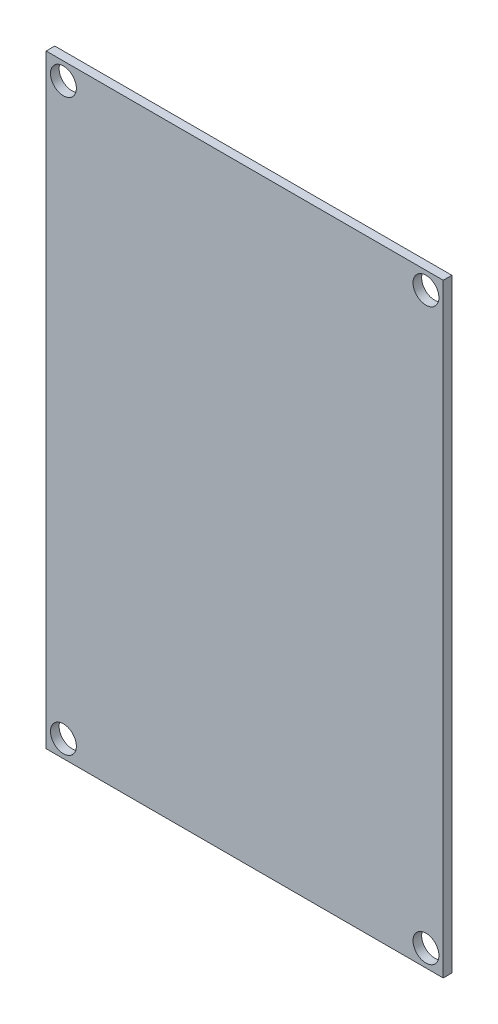
SolidWorks part; units mm, degrees
ref_plane "Alzado" through (0, 0, 0) normal (0, 0, 1) x (1, 0, 0)
ref_plane "Planta" through (0, 0, 0) normal (0, 1, 0) x (1, 0, 0)
ref_plane "Vista lateral" through (0, 0, 0) normal (1, 0, 0) x (0, 0, -1)
sketch "Croquis1" plane through (0, 0, 0) normal (0, 0, 1) x (1, 0, 0)
  line L1 (-23, -35) -> (23, -35)
  line L2 (-23, -35) -> (-23, 35)
  line L3 (-23, 35) -> (23, 35)
  line L4 (23, -35) -> (23, 35)
  line L5 (-23, -35) -> (23, 35) construction
  line L6 (-23, 35) -> (23, -35) construction
  point P0 (0, 0)
  dimension "D1" = 46
  dimension "D2" = 70
extrude "Saliente-Extruir1" add sketch "Croquis1" along normal blind 1
sketch "Croquis2" plane through (0, 0, 1) normal (0, 0, 1) x (1, 0, 0)
  line L0 (-23, -35) -> (23, -35) construction
  line L1 (-23, 35) -> (-23, -35) construction
  line L2 (23, -35) -> (23, 35) construction
  line L3 (23, 35) -> (-23, 35) construction
  circle A0 centre (-21, -33) radius 1.5
  circle A1 centre (21, -33) radius 1.5
  circle A2 centre (-21, 33) radius 1.5
  circle A3 centre (21, 33) radius 1.5
  dimension "D3" = 3
  dimension "D4" = 3
  dimension "D9" = 3
  dimension "D12" = 3
  dimension "D1" = 2
  dimension "D2" = 2
  dimension "D5" = 2
  dimension "D6" = 2
  dimension "D7" = 2
  dimension "D8" = 2
  dimension "D10" = 2
  dimension "D11" = 2
extrude "Cortar-Extruir1" cut sketch "Croquis2" against normal blind 1
